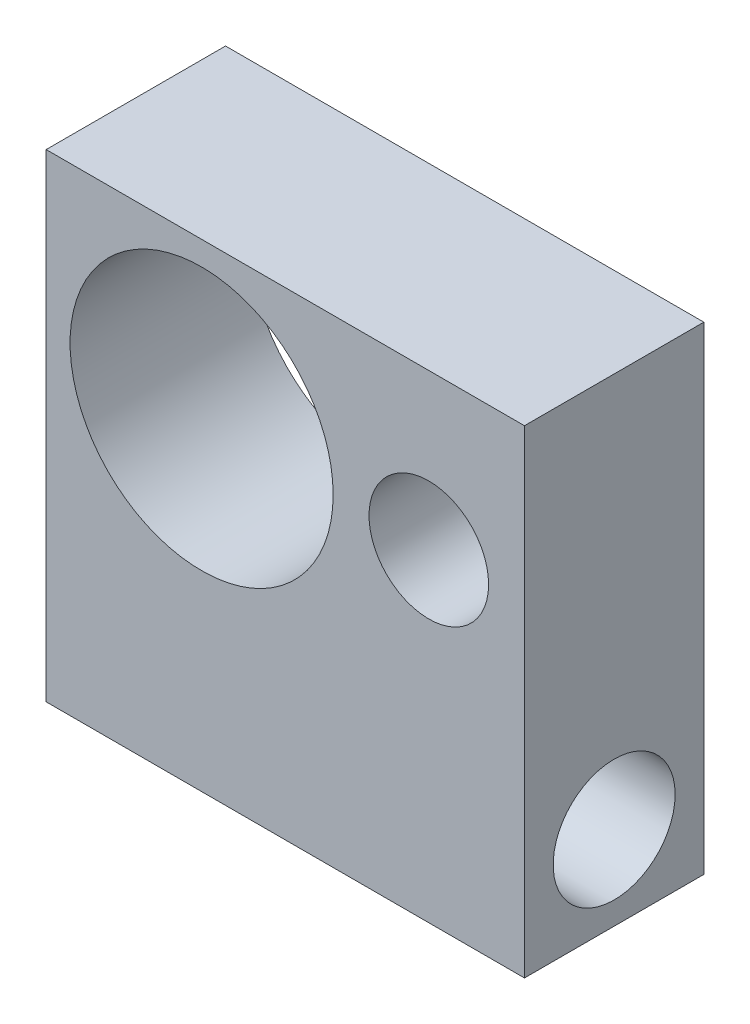
SolidWorks part; units mm, degrees
ref_plane "Front Plane" through (0, 0, 0) normal (0, 0, 1) x (1, 0, 0)
ref_plane "Top Plane" through (0, 0, 0) normal (0, 1, 0) x (1, 0, 0)
ref_plane "Right Plane" through (0, 0, 0) normal (1, 0, 0) x (0, 0, -1)
sketch "Sketch2" plane through (0, 0, 0) normal (0, 0, 1) x (1, 0, 0)
  line L1 (-20, -20) -> (20, -20)
  line L2 (-20, -20) -> (-20, 20)
  line L3 (-20, 20) -> (20, 20)
  line L4 (20, -20) -> (20, 20)
  line L5 (-20, -20) -> (20, 20) construction
  line L6 (-20, 20) -> (20, -20) construction
  circle A0 centre (12, 7) radius 5
  circle A1 centre (-7, 7) radius 11
  point P0 (0, 0)
  point P10 (0, 0)
  dimension "D3" = 22
  dimension "D4" = 10
  dimension "D6" = 8
  dimension "D7" = 13
  dimension "D1" = 40
  dimension "D2" = 40
  dimension "D5" = 0
extrude "Boss-Extrude1" add sketch "Sketch2" along normal blind 15
sketch "Sketch3" plane through (20, 0, 0) normal (1, 0, 0) x (0, 0, -1)
  line L0 (-15, -20) -> (0, -20) construction
  circle A0 centre (-7.5, -13) radius 5.1
  dimension "D1" = 10.2
  dimension "D2" = 7
extrude "Cut-Extrude1" cut sketch "Sketch3" against normal through all
